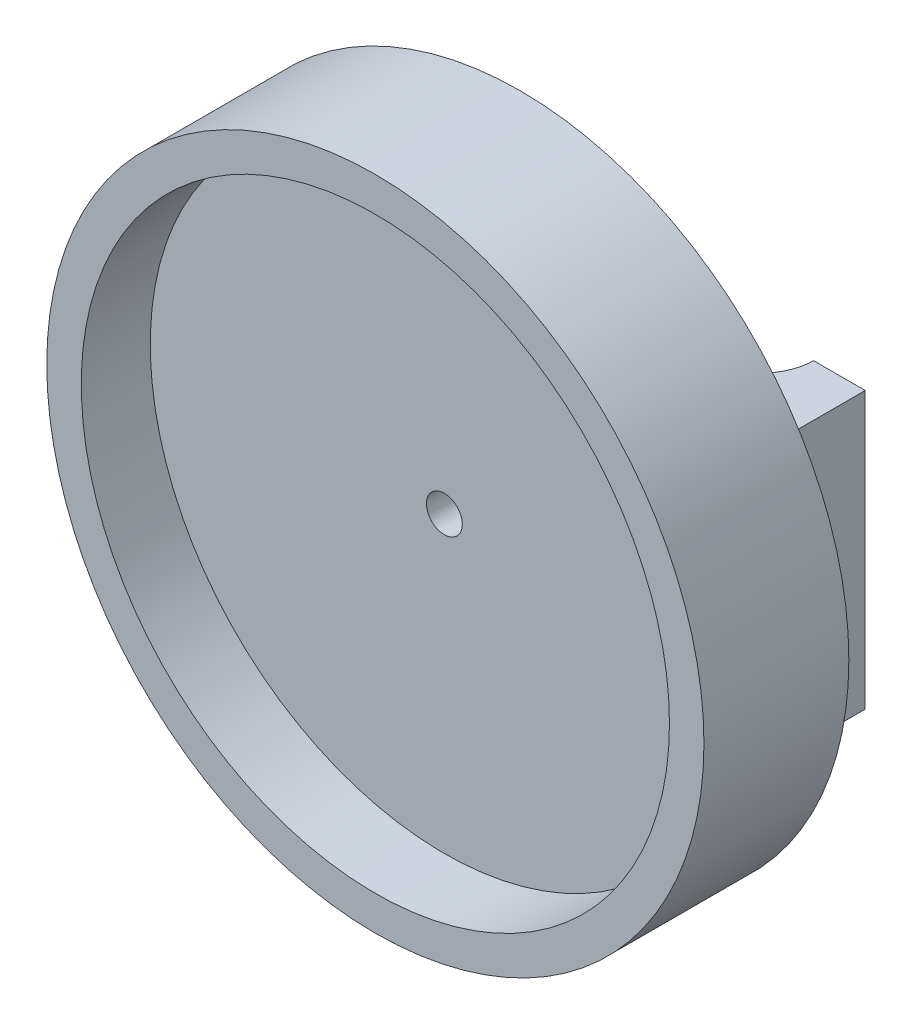
SolidWorks part; units mm, degrees
ref_plane "Front Plane" through (0, 0, 0) normal (0, 0, 1) x (1, 0, 0)
ref_plane "Top Plane" through (0, 0, 0) normal (0, 1, 0) x (1, 0, 0)
ref_plane "Right Plane" through (0, 0, 0) normal (1, 0, 0) x (0, 0, -1)
sketch "Sketch1" plane through (0, 0, 0) normal (0, 0, 1) x (1, 0, 0)
  circle A0 centre (0, 0) radius 47.625
  dimension "D1" = 95.25
extrude "Boss-Extrude1" add sketch "Sketch1" along normal blind 21
sketch "Sketch2" plane through (0, 0, 21) normal (0, 0, 1) x (1, 0, 0)
  circle A0 centre (0, 0) radius 42.625
  circle A1 centre (0, 0) radius 47.625 construction
  dimension "D1" = 5
extrude "Cut-Extrude1" cut sketch "Sketch2" against normal blind 10
sketch "Sketch3" plane through (0, 0, 0) normal (0, 0, -1) x (-1, 0, 0)
  line L1 (-35, -20) -> (35, -20)
  line L2 (-35, -20) -> (-35, 20)
  line L3 (-35, 20) -> (35, 20)
  line L4 (35, -20) -> (35, 20)
  dimension "D1" = 70
  dimension "D2" = 40
  dimension "D3" = 35
  dimension "D4" = 20
extrude "Boss-Extrude2" add sketch "Sketch3" along normal blind 15
sketch "Sketch4" plane through (0, 20, 0) normal (0, 1, 0) x (-1, 0, 0)
  line L2 (35, -15) -> (-35, -15) construction
  line L3 (35, -15) -> (35, 0) construction
  circle A0 centre (-20, -15) radius 7.5
  circle A1 centre (20, -15) radius 7.5
  dimension "D1" = 15
  dimension "D2" = 15
  dimension "D3" = 40
  dimension "D4" = 0
  dimension "D5" = 0
  dimension "D6" = 15
extrude "Cut-Extrude2" cut sketch "Sketch4" against normal through all
sketch "Sketch5" plane through (0, 0, -15) normal (0, 0, -1) x (-1, 0, 0)
  circle A0 centre (0, 0) radius 2.6
  dimension "D1" = 5.2
extrude "Cut-Extrude3" cut sketch "Sketch5" against normal through all
sketch "Sketch6" plane through (0, 0, 0) normal (0, 1, 0) x (1, 0, 0)
  circle A0 centre (-20, 15) radius 11.5
  circle A1 centre (20, 15) radius 11.5
  arc A2 (-27.5, 15) -> (-12.5, 15) centre (-20, 15) ccw construction
  arc A3 (12.5, 15) -> (27.5, 15) centre (20, 15) ccw construction
  dimension "D3" = 40
  dimension "D4" = 0
  dimension "D5" = 0
  dimension "D1" = 23
  dimension "D2" = 23
extrude "Cut-Extrude4" cut sketch "Sketch6" against normal mid plane 33
equation "\"D3@Sketch3\"=\"D1@Sketch3\"/2"
equation "\"D4@Sketch3\"=\"D2@Sketch3\"/2"
equation "\"D2@Sketch4\"=\"D1@Sketch4\""
equation "\"D2@Sketch6\"=\"D1@Sketch6\""
